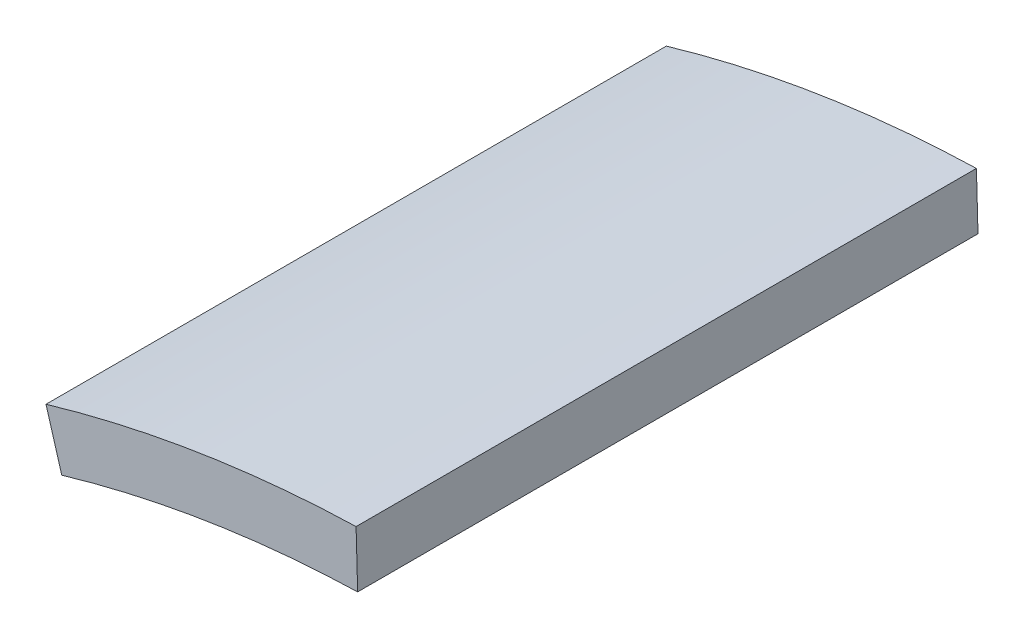
SolidWorks part; units mm, degrees
ref_plane "Ön Düzlem" through (0, 0, 0) normal (0, 0, 1) x (1, 0, 0)
ref_plane "Üst Düzlem" through (0, 0, 0) normal (0, 1, 0) x (1, 0, 0)
ref_plane "Sağ Düzlem" through (0, 0, 0) normal (1, 0, 0) x (0, 0, -1)
sketch "Model" plane through (0, 0, 0) normal (0, 0, 1) x (1, 0, 0)
  line L0 (-27.7776, 94.5021) -> (-26.5086, 90.1848)
  line L1 (-2.6574, 93.9624) -> (-2.7847, 98.4606)
  arc A0 (-2.7847, 98.4606) -> (-27.7776, 94.5021) centre (0, 0) ccw
  arc A1 (-2.6574, 93.9624) -> (-26.5086, 90.1848) centre (0, 0) ccw
  circle A2 centre (0, 0) radius 94 construction
extrude "Yükseklik-Ekstrüzyon1" add sketch "Model" along normal blind 100
ref_plane "Düzlem1" through (0, 0, 50) normal (0, 0, 1) x (1, 0, 0)
split "Ayır1" trim tools "Düzlem1" bodies to split 101 resulting bodies 102 103
delete or keep bodies "Gövde-Sil/Tut 1" type delete bodies bodies 103
